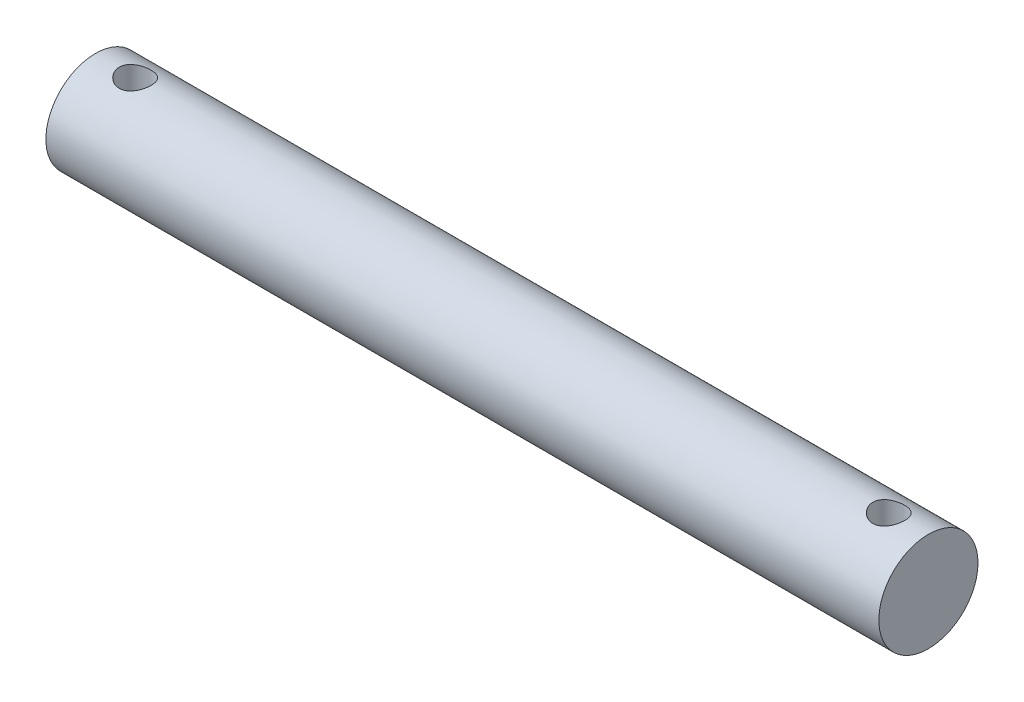
SolidWorks part; units mm, degrees
ref_plane "Front Plane" through (0, 0, 0) normal (0, 0, 1) x (1, 0, 0)
ref_plane "Top Plane" through (0, 0, 0) normal (0, 1, 0) x (1, 0, 0)
ref_plane "Right Plane" through (0, 0, 0) normal (1, 0, 0) x (0, 0, -1)
sketch "Sketch1" plane through (0, 0, 0) normal (1, 0, 0) x (0, 0, -1)
  circle A0 centre (0, 0) radius 12.5
  dimension "D1" = 25
extrude "Boss-Extrude1" add sketch "Sketch1" along normal blind 210
sketch "Sketch2" plane through (0, 0, 0) normal (0, 1, 0) x (1, 0, 0)
  line L0 (0, 12.5) -> (0, -12.5) construction
  line L1 (0, -12.5) -> (210, -12.5) construction
  line L2 (210, 12.5) -> (0, 12.5) construction
  line L3 (210, -12.5) -> (210, 12.5) construction
  circle A0 centre (10, 0) radius 4
  circle A1 centre (200, 0) radius 4
  dimension "D1" = 8
  dimension "D4" = 8
  dimension "D2" = 10
  dimension "D3" = 12.5
  dimension "D5" = 12.5
  dimension "D6" = 10
extrude "Cut-Extrude1" cut sketch "Sketch2" against normal through all and the other way through all
